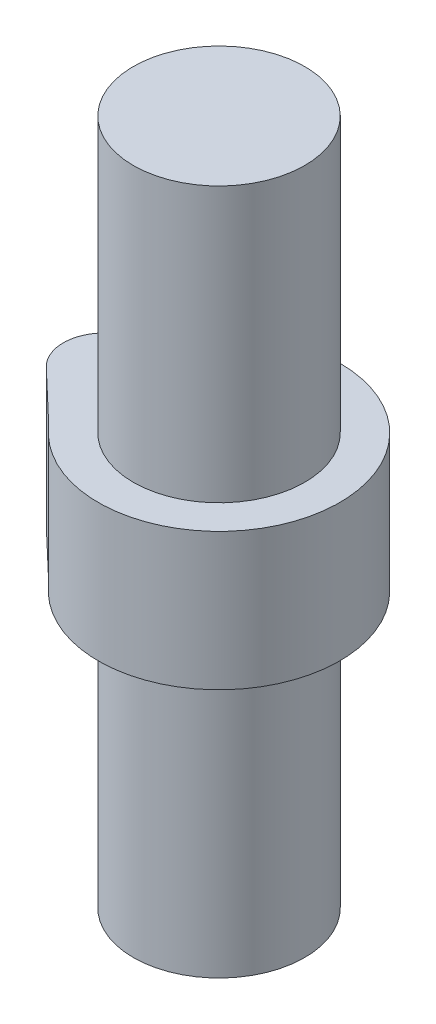
SolidWorks part; units mm, degrees
ref_plane "Piano frontale" through (0, 0, 0) normal (0, 0, 1) x (1, 0, 0)
ref_plane "Piano superiore" through (0, 0, 0) normal (0, 1, 0) x (1, 0, 0)
ref_plane "Piano destro" through (0, 0, 0) normal (1, 0, 0) x (0, 0, -1)
sketch "Schizzo1" plane through (0, 0, 0) normal (0, 1, 0) x (1, 0, 0)
  circle A0 centre (0, 0) radius 6.25
  dimension "D1" = 12.5
extrude "Estrusione-Estrusione1" add sketch "Schizzo1" along normal blind 20
sketch "Schizzo2" plane through (0, 20, 0) normal (0, 1, 0) x (1, 0, 0)
  line L0 (-6.25, 6.195) -> (-12.7, 0)
  line L1 (-12.7, 0) -> (-6.6574, -5.755)
  arc A0 (-6.6574, -5.755) -> (-6.25, 6.195) centre (0, 0) ccw
  dimension "D1" = 17.6
  dimension "D2" = 21.5
extrude "Estrusione-Estrusione2" add sketch "Schizzo2" along normal blind 10
fillet "Raccordo1" radius 3 1 edges at (-12.7, 25, 0)
sketch "Schizzo3" plane through (0, 30, 0) normal (0, 1, 0) x (1, 0, 0)
  circle A0 centre (0, 0) radius 6.25
  dimension "D1" = 12.5
extrude "Estrusione-Estrusione3" add sketch "Schizzo3" along normal blind 20
